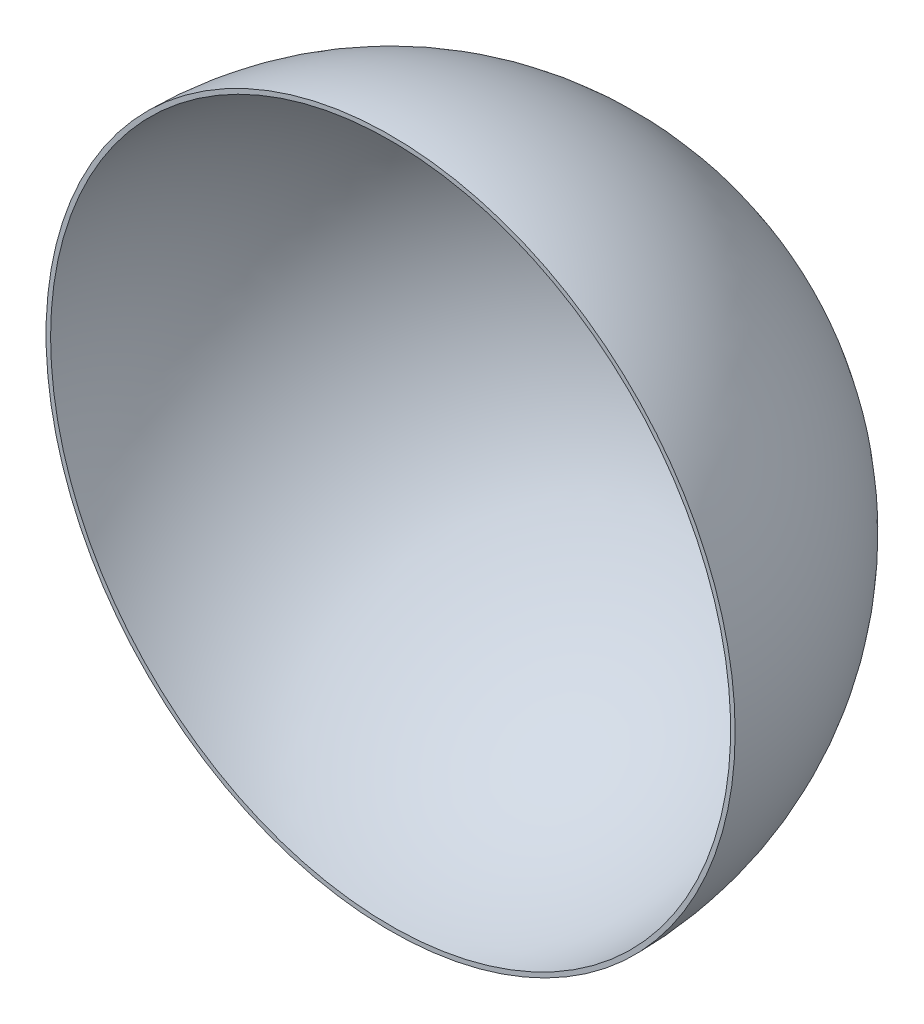
SolidWorks part; units mm, degrees
material "ABS PC"
ref_plane "Front Plane" through (0, 0, 0) normal (0, 0, 1) x (1, 0, 0)
ref_plane "Top Plane" through (0, 0, 0) normal (0, 1, 0) x (1, 0, 0)
ref_plane "Right Plane" through (0, 0, 0) normal (1, 0, 0) x (0, 0, -1)
sketch "Sketch2" plane through (0, 0, 0) normal (0, 0, 1) x (1, 0, 0)
  line L0 (0, -1000) -> (0, 49000) construction
  arc A0 (0, 380) -> (0, -380) centre (0, 0) cw
  dimension "D2" = 380
  dimension "D1" = 0
revolve "Revolve-Thin1" add sketch "Sketch2" angle 180 about L0
sketch "Sketch3" plane through (0, 0, 0) normal (0, 0, 1) x (1, 0, 0)
  point P0 (0, 0)
